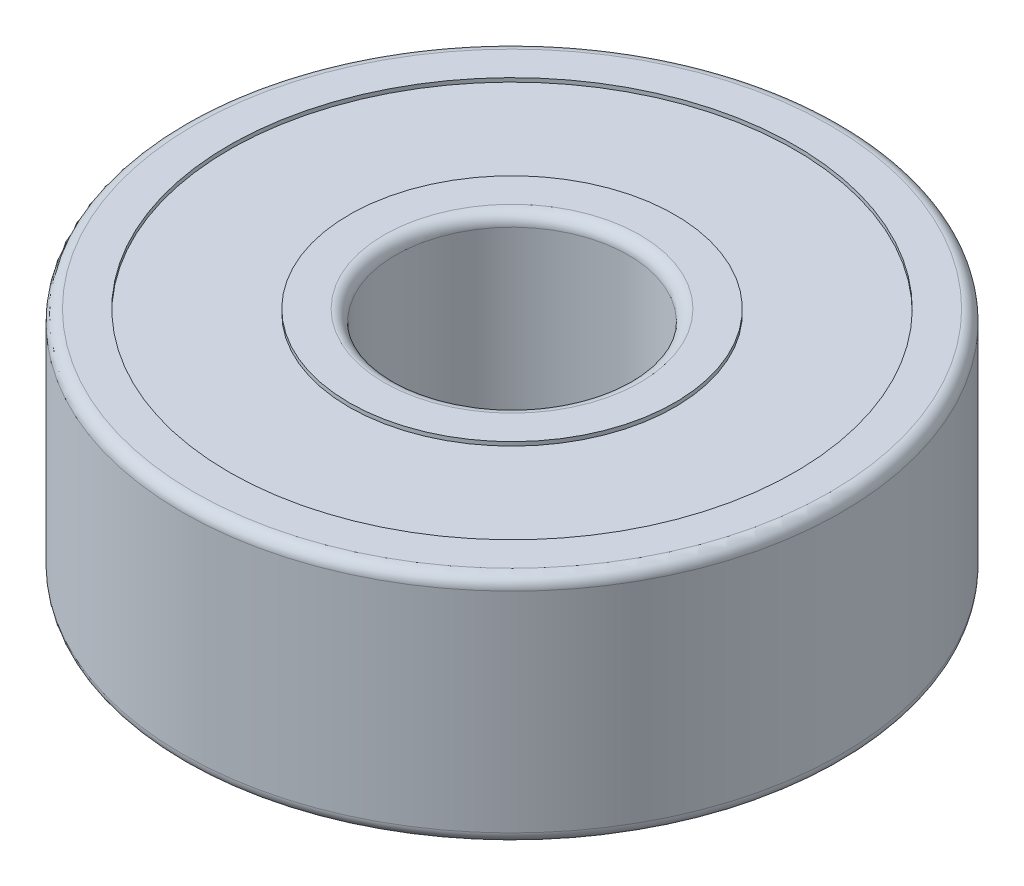
SolidWorks part; units mm, degrees
ref_plane "Alzado" through (0, 0, 0) normal (0, 0, 1) x (1, 0, 0)
ref_plane "Planta" through (0, 0, 0) normal (0, 1, 0) x (1, 0, 0)
ref_plane "Vista lateral" through (0, 0, 0) normal (1, 0, 0) x (0, 0, -1)
sketch "Croquis1" plane through (0, 0, 0) normal (0, 1, 0) x (1, 0, 0)
  circle A0 centre (0, 0) radius 3
  circle A1 centre (0, 0) radius 8.5
  dimension "D1" = 17
  dimension "D2" = 6
extrude "Saliente-Extruir1" add sketch "Croquis1" along normal blind 6
sketch "Croquis2" plane through (0, 6, 0) normal (0, 1, 0) x (1, 0, 0)
  circle A0 centre (0, 0) radius 7.3
  circle A1 centre (0, 0) radius 4.2
  circle A2 centre (0, 0) radius 3 construction
  circle A3 centre (0, 0) radius 8.5 construction
  dimension "D1" = 1.2
  dimension "D2" = 1.2
extrude "Cortar-Extruir1" cut sketch "Croquis2" against normal blind 0.1
ref_plane "Plano1" through (0, 3, 0) normal (0, 1, 0) x (1, 0, 0)
mirror "Simetría1" about plane through (0, 3, 0) normal (0, 1, 0) of "Cortar-Extruir1"
fillet "Redondeo1" radius 0.3 4 edges at (0, 0, 8.5) (0, 6, 8.5) (0, 0, 3) (0, 6, 3)
